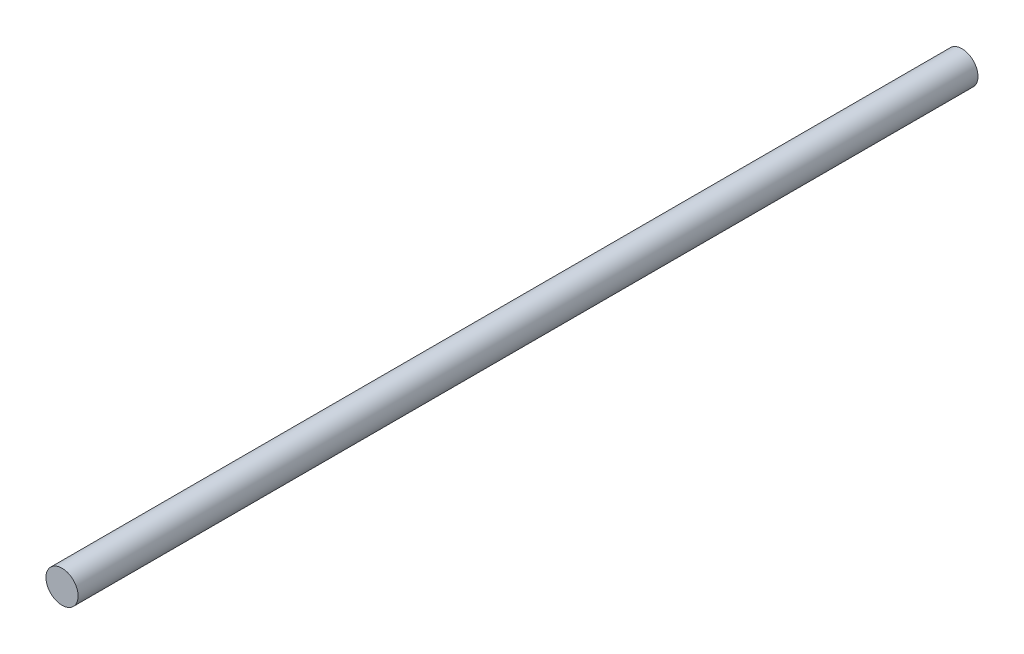
SolidWorks part; units mm, degrees
ref_plane "Front Plane" through (0, 0, 0) normal (0, 0, 1) x (1, 0, 0)
ref_plane "Top Plane" through (0, 0, 0) normal (0, 1, 0) x (1, 0, 0)
ref_plane "Right Plane" through (0, 0, 0) normal (1, 0, 0) x (0, 0, -1)
sketch "Sketch1" plane through (0, 0, 0) normal (0, 0, 1) x (1, 0, 0)
  circle A0 centre (0, 0) radius 6.35
  dimension "D1" = 12.7
extrude "Boss-Extrude1" add sketch "Sketch1" along normal blind 355.6
